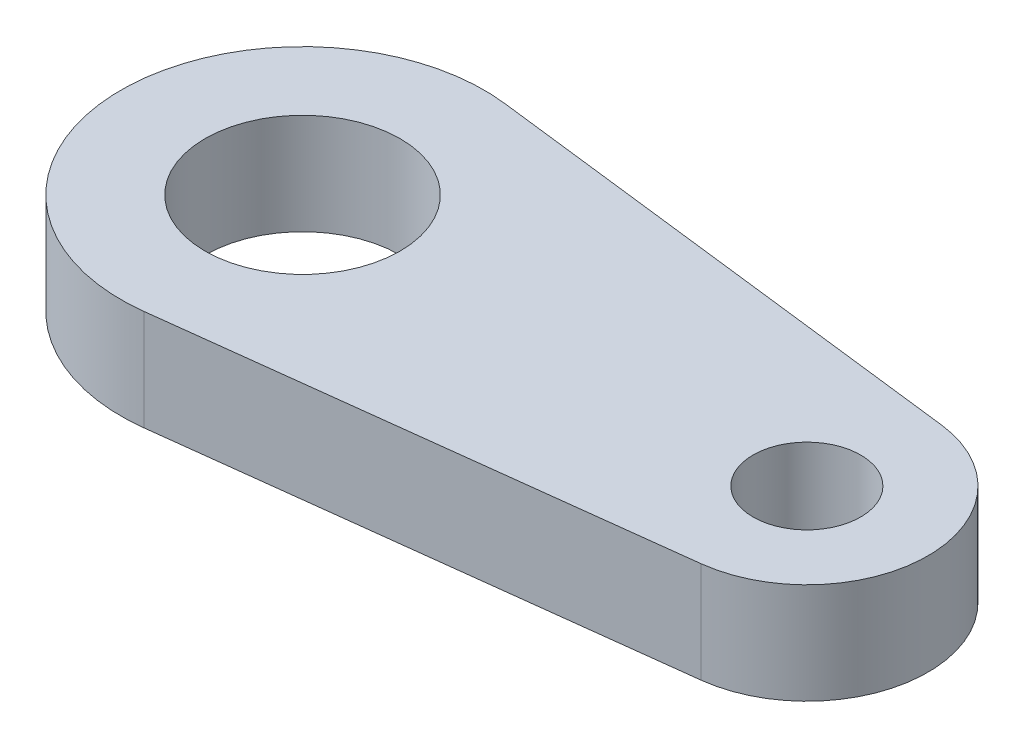
SolidWorks part; units mm, degrees
ref_plane "Front Plane" through (0, 0, 0) normal (0, 0, 1) x (1, 0, 0)
ref_plane "Top Plane" through (0, 0, 0) normal (0, 1, 0) x (1, 0, 0)
ref_plane "Right Plane" through (0, 0, 0) normal (1, 0, 0) x (0, 0, -1)
sketch "Sketch1" plane through (0, 0, 0) normal (0, 1, 0) x (1, 0, 0)
  line L0 (0.648, 5.361) -> (15.432, 3.574)
  line L1 (15.432, -3.574) -> (0.648, -5.361)
  arc A0 (0.648, 5.361) -> (0.648, -5.361) centre (0, 0) ccw
  arc A1 (15.432, -3.574) -> (15.432, 3.574) centre (15, 0) ccw
  dimension "D2" = 5.4
  dimension "D3" = 3.6
  dimension "D1" = 15
extrude "Boss-Extrude1" add sketch "Sketch1" along normal blind 3
sketch "Sketch2" plane through (0, 3, 0) normal (0, 1, 0) x (1, 0, 0)
  circle A0 centre (0, 0) radius 2.9
  circle A1 centre (15, 0) radius 1.6
  dimension "D1" = 5.8
  dimension "D2" = 3.2
extrude "Cut-Extrude1" cut sketch "Sketch2" against normal through all
